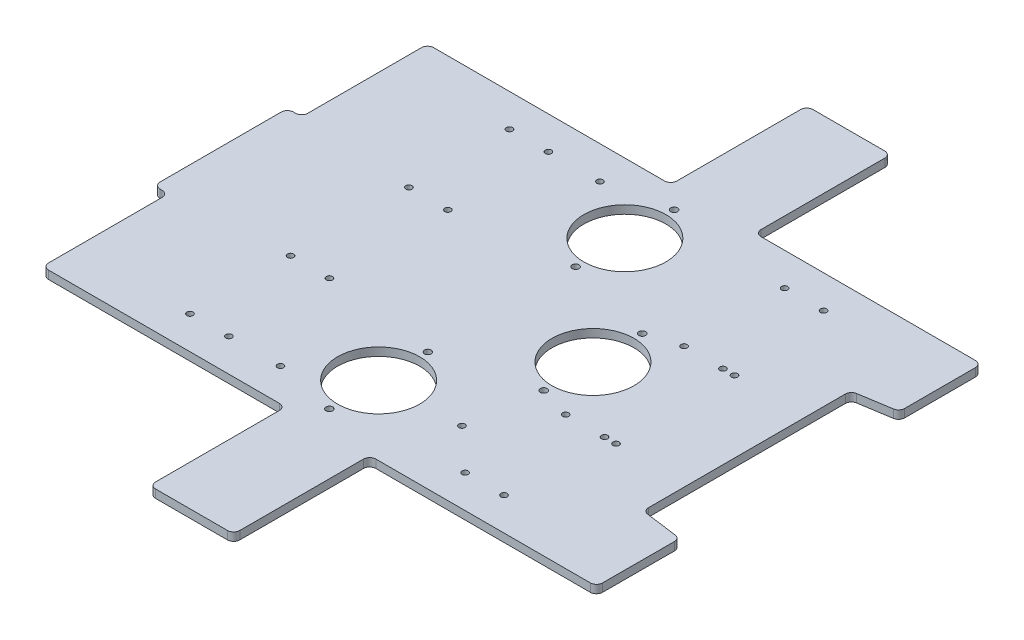
SolidWorks part; units mm, degrees
ref_plane "Front Plane" through (0, 0, 0) normal (0, 0, 1) x (1, 0, 0)
ref_plane "Top Plane" through (0, 0, 0) normal (0, 1, 0) x (1, 0, 0)
ref_plane "Right Plane" through (0, 0, 0) normal (1, 0, 0) x (0, 0, -1)
sketch "Sketch1" plane through (0, 0, 0) normal (0, 1, 0) x (1, 0, 0)
  line L4 (187.6801, 0) -> (-187.9931, 0) construction
  line L13 (92.4587, 93.85) -> (92.4587, 53.8038)
  line L14 (92.4587, 53.8038) -> (71.9148, 50.55)
  line L15 (92.5282, -53.3294) -> (71.9148, -50.55)
  line L16 (92.4587, -93.85) -> (92.5282, -53.3294)
  line L17 (71.9148, 50.55) -> (71.9148, -50.55)
  line L18 (-59.0413, 93.85) -> (-59.0413, 160.15)
  line L19 (-59.0413, 160.15) -> (-18.0413, 160.15)
  line L20 (-18.0413, 160.15) -> (-18.0413, 93.85)
  line L21 (-59.0413, 93.85) -> (-177.5413, 93.85)
  line L22 (-18.0413, 93.85) -> (92.4587, 93.85)
  line L23 (-18.0413, -93.85) -> (92.4587, -93.85)
  line L24 (-18.0413, -160.15) -> (-18.0413, -93.85)
  line L25 (-59.0413, -160.15) -> (-18.0413, -160.15)
  line L26 (-59.0413, -93.85) -> (-59.0413, -160.15)
  line L27 (-59.0413, -93.85) -> (-177.5413, -93.85)
  line L31 (-177.5413, 93.85) -> (-177.5413, 34.2746)
  line L32 (-177.5413, 34.2746) -> (-177.5413, 32.5)
  line L33 (-184.5413, -32.5) -> (-184.5413, 32.5)
  line L34 (-184.5413, 32.5) -> (-177.5413, 32.5)
  line L35 (-184.5413, -32.5) -> (-177.5413, -32.5)
  line L36 (-177.5413, -32.5) -> (-177.5413, -93.85)
  circle A0 centre (-47.5413, 60) radius 20
  circle A1 centre (-3.0852, 0) radius 20
  circle A2 centre (-47.5413, -60) radius 20
  circle A3 centre (-77.5413, 77.85) radius 1.5
  circle A4 centre (-121.6213, 28.85) radius 1.5
  circle A5 centre (-102.6513, 28.85) radius 1.5
  circle A6 centre (-121.6213, -28.85) radius 1.5
  circle A7 centre (-102.6513, -28.85) radius 1.5
  circle A8 centre (-77.5413, -77.85) radius 1.5
  circle A9 centre (37.0248, 28.85) radius 1.5
  circle A10 centre (12.4587, 77.85) radius 1.5
  circle A11 centre (-8.0852, -58.85) radius 1.5
  circle A12 centre (12.4587, -77.85) radius 1.5
  circle A13 centre (37.0248, -28.85) radius 1.5
  circle A14 centre (-121.6213, -77.85) radius 1.5
  circle A15 centre (-102.6513, -77.85) radius 1.5
  circle A16 centre (31.4287, -77.85) radius 1.5
  circle A17 centre (12.4448, -28.85) radius 1.5
  circle A18 centre (31.4148, -28.85) radius 1.5
  circle A19 centre (-121.6213, 77.85) radius 1.5
  circle A20 centre (-102.6513, 77.85) radius 1.5
  circle A21 centre (31.4148, 28.85) radius 1.5
  circle A22 centre (12.4448, 28.85) radius 1.5
  circle A23 centre (31.4287, 77.85) radius 1.5
  circle A24 centre (-47.5413, -84) radius 1.65
  circle A25 centre (-47.5413, -36) radius 1.65
  circle A26 centre (-3.0852, -24) radius 1.65
  circle A27 centre (-3.0852, 24) radius 1.65
  circle A28 centre (-47.5413, 36) radius 1.65
  circle A29 centre (-47.5413, 84) radius 1.65
  point P37 (-184.5413, 0)
  dimension "D12" = 40
  dimension "D13" = 40
  dimension "D14" = 100.15
  dimension "D16" = 75
  dimension "D17" = 93.85
  dimension "D18" = 3
  dimension "D19" = 16
  dimension "D20" = 100
  dimension "D21" = 65
  dimension "D22" = 65
  dimension "D23" = 81.89
  dimension "D24" = 34.89
  dimension "D25" = 16
  dimension "D26" = 80
  dimension "D27" = 35
  dimension "D28" = 80
  dimension "D30" = 80.0273
  dimension "D31" = 65
  dimension "D32" = 62.92
  dimension "D33" = 3
  dimension "D34" = 3
  dimension "D35" = 3
  dimension "D36" = 3
  dimension "D37" = 3
  dimension "D40" = 3
  dimension "D41" = 3
  dimension "D44" = 49
  dimension "D45" = 18.97
  dimension "D46" = 49
  dimension "D47" = 3
  dimension "D48" = 3
  dimension "D49" = 3
  dimension "D50" = 16
  dimension "D51" = 16
  dimension "D52" = 40.5
  dimension "D53" = 3.3
  dimension "D54" = 3.3
  dimension "D55" = 3.3
  dimension "D56" = 3.3
  dimension "D57" = 3.3
  dimension "D58" = 3.3
  dimension "D1" = 187.7
  dimension "D2" = 270
  dimension "D3" = 20.8
  dimension "D4" = 99
  dimension "D5" = 101.1
  dimension "D6" = 20.8
  dimension "D7" = 66.3
  dimension "D8" = 41
  dimension "D9" = 110.5
  dimension "D10" = 32.5
  dimension "D11" = 7
  dimension "D15" = 130
  dimension "D29" = 177.5413
  dimension "D38" = 49
  dimension "D39" = 49
  dimension "D42" = 18.97
  dimension "D43" = 18.97
extrude "Boss-Extrude2" add sketch "Sketch1" along normal blind 4
fillet "Fillet1" radius 3 20 edges at (-177.5413, 2, -93.85) (-184.5413, 2, -32.5) (-177.5413, 2, -32.5) (-184.5413, 2, 32.5) (-177.5413, 2, 32.5) (-177.5413, 2, 93.85) (-59.0413, 2, 93.85) (-59.0413, 2, 160.15) (-18.0413, 2, 160.15) (-18.0413, 2, 93.85) (92.4587, 2, 93.85) (92.5282, 2, 53.3294) (71.9148, 2, 50.55) (71.9148, 2, -50.55) (92.4587, 2, -53.8038) (92.4587, 2, -93.85) (-59.0413, 2, -93.85) (-18.0413, 2, -93.85) (-18.0413, 2, -160.15) (-59.0413, 2, -160.15)
